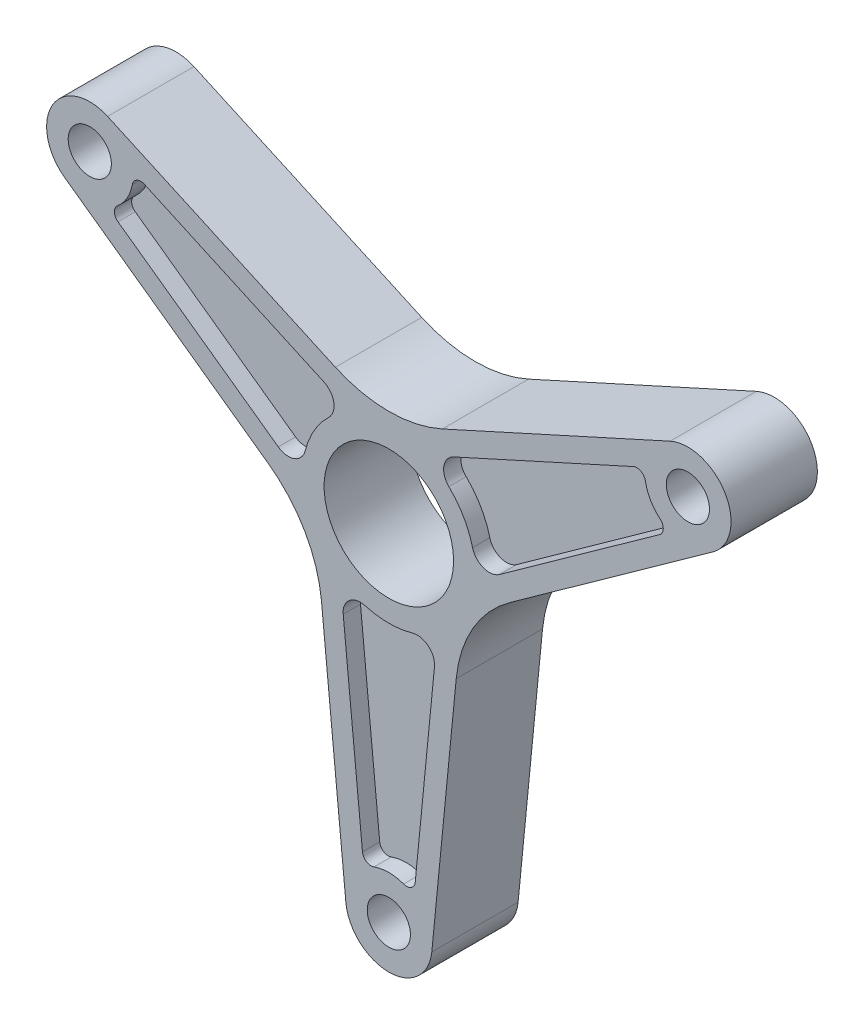
SolidWorks part; units mm, degrees
ref_plane "Front Plane" through (0, 0, 0) normal (0, 0, 1) x (1, 0, 0)
ref_plane "Top Plane" through (0, 0, 0) normal (0, 1, 0) x (1, 0, 0)
ref_plane "Right Plane" through (0, 0, 0) normal (1, 0, 0) x (0, 0, -1)
sketch "Sketch2" plane through (0, 0, 0) normal (0, 0, 1) x (1, 0, 0)
  line L0 (0, 0) -> (0, -80) construction
  line L1 (-9.9522, -80.9766) -> (-15.6097, -23.3203)
  line L2 (9.9522, -80.9766) -> (15.6097, -23.3203)
  line L3 (-65.1517, 49.1071) -> (-12.3911, 25.1786)
  line L4 (-75.1039, 31.8694) -> (-28.0009, -1.8583)
  line L5 (75.1039, 31.8694) -> (28.0009, -1.8583)
  line L6 (65.1517, 49.1071) -> (12.3911, 25.1786)
  circle A9 centre (0, 0) radius 22.5 construction
  circle A10 centre (0, 0) radius 15
  circle A11 centre (0, -80) radius 5
  arc A12 (-9.9522, -80.9766) -> (9.9522, -80.9766) centre (0, -80) ccw
  circle A13 centre (-69.282, 40) radius 5
  arc A14 (-65.1517, 49.1071) -> (-75.1039, 31.8694) centre (-69.282, 40) ccw
  circle A15 centre (69.282, 40) radius 5
  arc A16 (75.1039, 31.8694) -> (65.1517, 49.1071) centre (69.282, 40) ccw
  arc A17 (-28.0009, -1.8583) -> (-15.6097, -23.3203) centre (-45.4663, -26.25) cw
  arc A18 (12.3911, 25.1786) -> (-12.3911, 25.1786) centre (0, 52.5) cw
  arc A19 (15.6097, -23.3203) -> (28.0009, -1.8583) centre (45.4663, -26.25) cw
  dimension "D1" = 45
  dimension "D2" = 30
  dimension "D3" = 80
  dimension "D4" = 20
  dimension "D7" = 3
  dimension "D5" = 10
  dimension "D6" = 30
extrude "Boss-Extrude1" add sketch "Sketch2" along normal blind 20
sketch "Sketch3" plane through (0, 0, 20) normal (0, 0, 1) x (1, 0, 0)
  line L0 (-10.5712, -23.468) -> (-6.1108, -68.9249)
  line L1 (-15.6097, -23.3203) -> (-9.9522, -80.9766) construction
  line L2 (0, 0) -> (0, -85) construction
  line L3 (10.5712, -23.468) -> (6.1108, -68.9249)
  line L4 (9.9522, -80.9766) -> (15.6097, -23.3203) construction
  line L5 (-25.6095, 2.5791) -> (-62.7461, 29.1704)
  line L6 (-15.0383, 20.889) -> (-56.6353, 39.7545)
  line L7 (15.0383, 20.889) -> (56.6353, 39.7545)
  line L8 (25.6095, 2.5791) -> (62.7461, 29.1704)
  circle A0 centre (0, -80) radius 5 construction
  arc A1 (-3.4336, -70.608) -> (3.4336, -70.608) centre (0, -80) cw
  arc A2 (-5.4919, -19.2312) -> (5.4919, -19.2312) centre (0, 0) ccw
  arc A3 (10.5712, -23.468) -> (5.4919, -19.2312) centre (6.5903, -23.0774) ccw
  arc A4 (-5.4919, -19.2312) -> (-10.5712, -23.468) centre (-6.5903, -23.0774) ccw
  arc A5 (6.1108, -68.9249) -> (3.4336, -70.608) centre (4.1203, -68.7296) cw
  arc A6 (-6.1108, -68.9249) -> (-3.4336, -70.608) centre (-4.1203, -68.7296) ccw
  arc A7 (-62.7461, 29.1704) -> (-62.8651, 32.3304) centre (-61.5817, 30.7965) cw
  arc A8 (-25.6095, 2.5791) -> (-19.4007, 4.8594) centre (-23.2808, 5.8313) ccw
  arc A9 (-59.4315, 38.2776) -> (-62.8651, 32.3304) centre (-69.282, 40) cw
  arc A10 (-56.6353, 39.7545) -> (-59.4315, 38.2776) centre (-57.4614, 37.9331) ccw
  arc A11 (-13.9087, 14.3718) -> (-15.0383, 20.889) centre (-16.6905, 17.2461) ccw
  arc A12 (-13.9087, 14.3718) -> (-19.4007, 4.8594) centre (0, 0) ccw
  arc A13 (56.6353, 39.7545) -> (59.4315, 38.2776) centre (57.4614, 37.9331) cw
  arc A14 (15.0383, 20.889) -> (13.9087, 14.3718) centre (16.6905, 17.2461) ccw
  arc A15 (62.8651, 32.3304) -> (59.4315, 38.2776) centre (69.282, 40) cw
  arc A16 (62.7461, 29.1704) -> (62.8651, 32.3304) centre (61.5817, 30.7965) ccw
  arc A17 (19.4007, 4.8594) -> (25.6095, 2.5791) centre (23.2808, 5.8313) ccw
  arc A18 (19.4007, 4.8594) -> (13.9087, 14.3718) centre (0, 0) ccw
  point P17 (11.2515, -16.5349)
  point P20 (-11.2515, -16.5349)
  point P23 (5.8218, -71.8694)
  point P26 (-5.8218, -71.8694)
  dimension "D1" = 20
  dimension "D2" = 10
  dimension "D4" = 4
  dimension "D5" = 2
  dimension "D3" = 5
extrude "Cut-Extrude1" cut sketch "Sketch3" against normal blind 4
sketch "Sketch4" plane through (0, 0, 0) normal (0, 0, -1) x (-1, 0, 0)
  line L0 (-10.5712, -23.468) -> (-6.1108, -68.9249)
  line L1 (-9.9522, -80.9766) -> (-15.6097, -23.3203) construction
  line L2 (0, 0) -> (0, -85) construction
  line L3 (10.5712, -23.468) -> (6.1108, -68.9249)
  line L4 (-25.6095, 2.5791) -> (-62.7461, 29.1704)
  line L5 (-15.0383, 20.889) -> (-56.6353, 39.7545)
  line L6 (15.0383, 20.889) -> (56.6353, 39.7545)
  line L7 (25.6095, 2.5791) -> (62.7461, 29.1704)
  circle A0 centre (0, -80) radius 5 construction
  arc A1 (-3.4336, -70.608) -> (3.4336, -70.608) centre (0, -80) cw
  arc A2 (-5.4919, -19.2312) -> (5.4919, -19.2312) centre (0, 0) ccw
  arc A3 (6.1108, -68.9249) -> (3.4336, -70.608) centre (4.1203, -68.7296) cw
  arc A4 (-3.4336, -70.608) -> (-6.1108, -68.9249) centre (-4.1203, -68.7296) cw
  arc A5 (10.5712, -23.468) -> (5.4919, -19.2312) centre (6.5903, -23.0774) ccw
  arc A6 (-10.5712, -23.468) -> (-5.4919, -19.2312) centre (-6.5903, -23.0774) cw
  arc A7 (-25.6095, 2.5791) -> (-19.4007, 4.8594) centre (-23.2808, 5.8313) ccw
  arc A8 (-62.7461, 29.1704) -> (-62.8651, 32.3304) centre (-61.5817, 30.7965) cw
  arc A9 (-59.4315, 38.2776) -> (-62.8651, 32.3304) centre (-69.282, 40) cw
  arc A10 (-59.4315, 38.2776) -> (-56.6353, 39.7545) centre (-57.4614, 37.9331) cw
  arc A11 (-15.0383, 20.889) -> (-13.9087, 14.3718) centre (-16.6905, 17.2461) cw
  arc A12 (-13.9087, 14.3718) -> (-19.4007, 4.8594) centre (0, 0) ccw
  arc A13 (15.0383, 20.889) -> (13.9087, 14.3718) centre (16.6905, 17.2461) ccw
  arc A14 (56.6353, 39.7545) -> (59.4315, 38.2776) centre (57.4614, 37.9331) cw
  arc A15 (62.8651, 32.3304) -> (59.4315, 38.2776) centre (69.282, 40) cw
  arc A16 (62.8651, 32.3304) -> (62.7461, 29.1704) centre (61.5817, 30.7965) cw
  arc A17 (25.6095, 2.5791) -> (19.4007, 4.8594) centre (23.2808, 5.8313) cw
  arc A18 (19.4007, 4.8594) -> (13.9087, 14.3718) centre (0, 0) ccw
  point P20 (5.8218, -71.8694)
  point P23 (-5.8218, -71.8694)
  point P26 (11.2515, -16.5349)
  point P29 (-11.2515, -16.5349)
  dimension "D2" = 20
  dimension "D3" = 10
  dimension "D4" = 2
  dimension "D5" = 4
  dimension "D1" = 5
extrude "Cut-Extrude2" cut sketch "Sketch4" against normal blind 4
